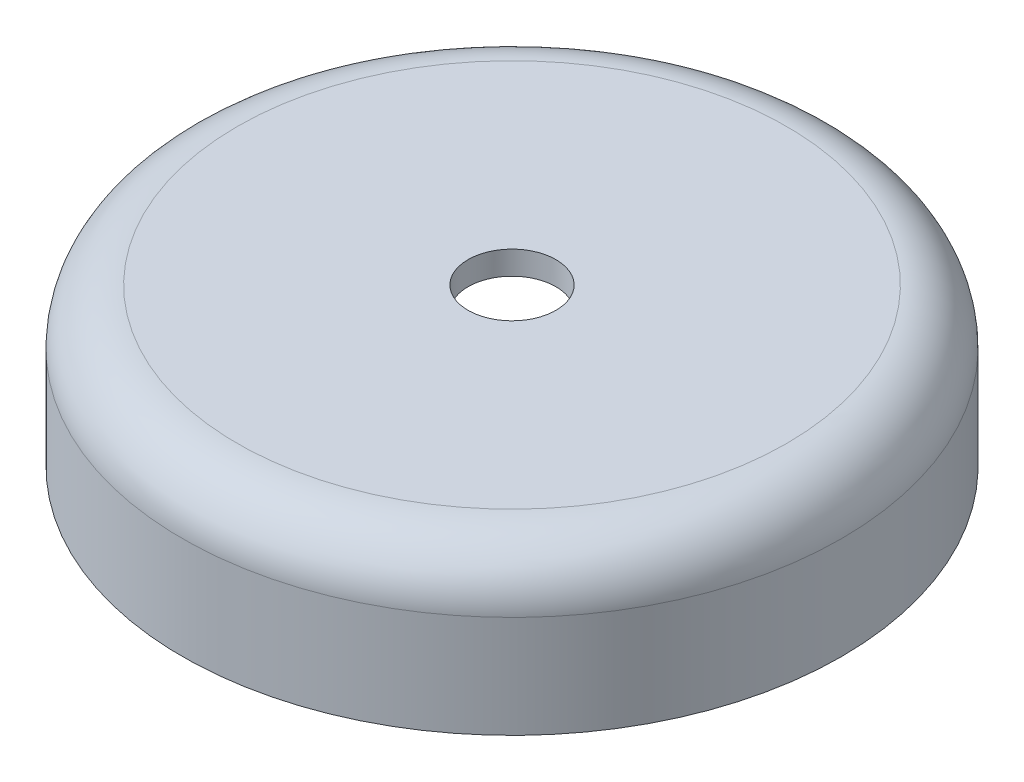
SolidWorks part; units mm, degrees
ref_plane "Face" through (0, 0, 0) normal (0, 0, 1) x (1, 0, 0)
ref_plane "Dessus" through (0, 0, 0) normal (0, 1, 0) x (1, 0, 0)
ref_plane "Droite" through (0, 0, 0) normal (1, 0, 0) x (0, 0, -1)
sketch "Esquisse2" plane through (0, 0, 0) normal (0, 0, 1) x (1, 0, 0)
  line L0 (0, 0) -> (0, -88.3722) construction
  line L1 (0, 0) -> (-25, 0)
  line L2 (0, 0) -> (0, -2.14)
  line L3 (0, -2.14) -> (-23.86, -2.14)
  line L4 (-30, -5) -> (-30, -14.3)
  line L5 (-30, -14.3) -> (-27.86, -14.3)
  line L6 (-27.86, -14.3) -> (-27.86, -6.14)
  arc A0 (-27.86, -6.14) -> (-23.86, -2.14) centre (-23.86, -6.14) cw
  arc A1 (-30, -5) -> (-25, 0) centre (-25, -5) cw
  dimension "D5" = 4
  dimension "D6" = 5
  dimension "D1" = 30
  dimension "D2" = 27.86
  dimension "D3" = 2.14
  dimension "D4" = 14.3
revolve "Révolution1" add sketch "Esquisse2" angle 360 about L0
sketch "Esquisse3" plane through (0, 0, 0) normal (0, 1, 0) x (1, 0, 0)
  circle A0 centre (0, 0) radius 4
  dimension "D1" = 8
extrude "Enlèv. mat.-Extru.1" cut sketch "Esquisse3" against normal up to next
